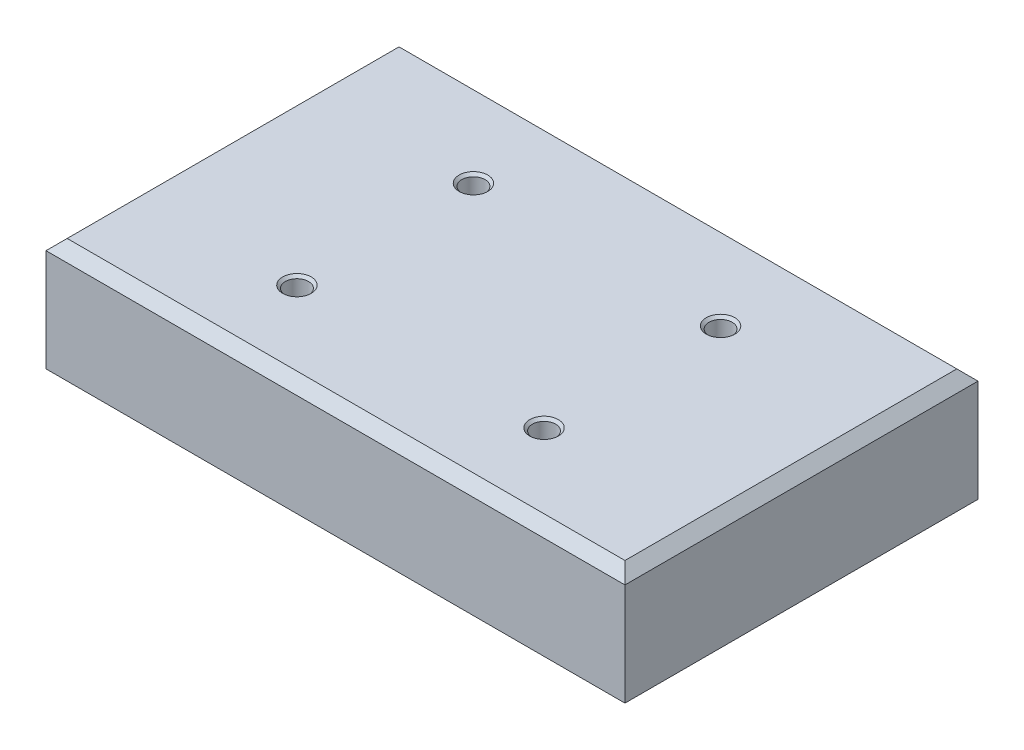
SolidWorks part; units mm, degrees
material "Oak"
ref_plane "Front Plane" through (0, 0, 0) normal (0, 0, 1) x (1, 0, 0)
ref_plane "Top Plane" through (0, 0, 0) normal (0, 1, 0) x (1, 0, 0)
ref_plane "Right Plane" through (0, 0, 0) normal (1, 0, 0) x (0, 0, -1)
sketch "Sketch1" plane through (0, 0, 0) normal (0, 1, 0) x (1, 0, 0)
  line L1 (-41, 25) -> (41, 25)
  line L2 (-41, 25) -> (-41, -25)
  line L3 (-41, -25) -> (41, -25)
  line L4 (41, 25) -> (41, -25)
  line L5 (-41, 25) -> (41, -25) construction
  line L6 (-41, -25) -> (41, 25) construction
  point P0 (0, 0)
  dimension "D1" = 82
  dimension "D2" = 50
extrude "Boss-Extrude1" add sketch "Sketch1" along normal blind 16
hole_wizard "M4 Tapped Hole2" positions "Sketch4" profile "Sketch5" tap size "M4" standard "DIN"
sketch "Sketch4" plane through (0, 16, 0) normal (0, 1, 0) x (1, 0, 0)
  point P0 (-17.5, 12.0394)
  point P2 (17.5, 12.0394)
  point P4 (17.5, -12.9606)
  point P6 (-17.5, -12.9606)
  dimension "D1" = 35
  dimension "D2" = 17.5
  dimension "D3" = 25
sketch "Sketch5" plane through (-17.5, 16, -12.0394) normal (1, 0, 0) x (0, 0, 1)
  line L0 (0, 0) -> (0, 8.9914)
  line L1 (0, 8.9914) -> (1.65, 8)
  line L2 (1.65, 8) -> (1.65, 0.375)
  line L3 (1.65, 0.375) -> (2.025, 0)
  line L5 (2.025, 0) -> (0, 0)
  line L6 (-1.65, 0.375) -> (-2.025, 0) construction
  line L10 (0, 8.9914) -> (-1.65, 8) construction
  line L11 (0, -6.35) -> (0, 107.95) construction
  dimension "Tap Drill Dia." = 3.3
  dimension "Tap Drill Depth" = 8
  dimension "Near C'Sink Dia." = 4.05
  dimension "Near C'Sink Angle" = 90
  dimension "Drill Angle" = 118
cosmetic thread "Hole Thread7" parameters "D1"=6, "D2"=4
cosmetic thread "Hole Thread8" parameters "D1"=6, "D2"=4
cosmetic thread "Hole Thread9" parameters "D1"=6, "D2"=4
cosmetic thread "Hole Thread10" parameters "D1"=6, "D2"=4
chamfer "Chamfer1" distance 1.5 angle 45 4 edges at (-41, 16, 0) (0, 16, -25) (41, 16, 0) (0, 16, 25)
